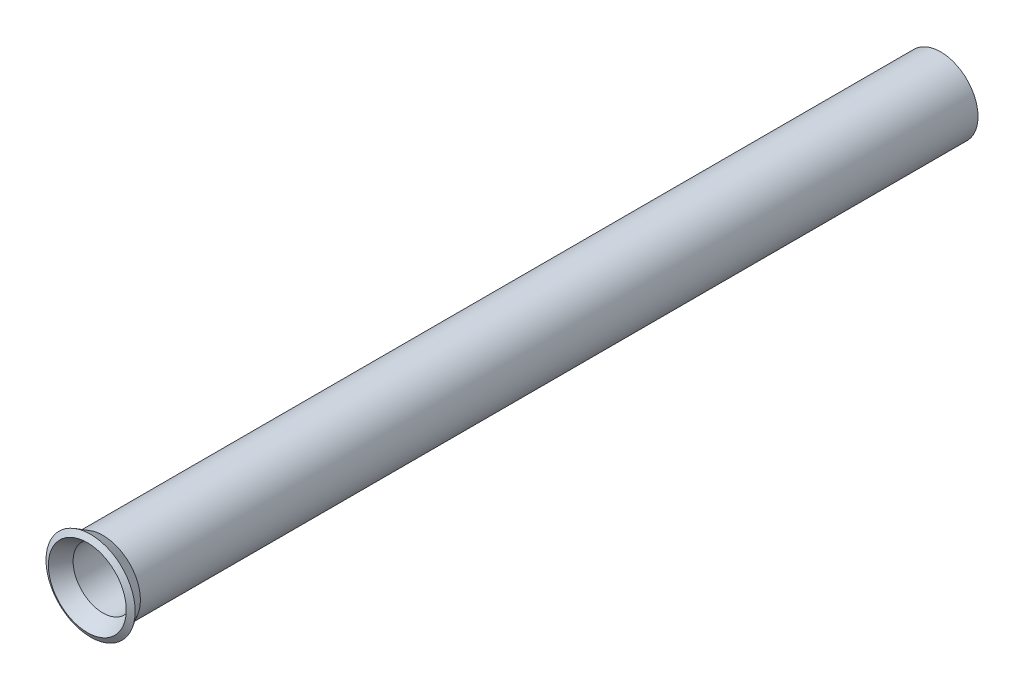
SolidWorks part; units mm, degrees
material "Stainless Steel (ferritic)"
ref_plane "Front Plane" through (0, 0, 0) normal (0, 0, 1) x (1, 0, 0)
ref_plane "Top Plane" through (0, 0, 0) normal (0, 1, 0) x (1, 0, 0)
ref_plane "Right Plane" through (0, 0, 0) normal (1, 0, 0) x (0, 0, -1)
sketch "Sketch1" plane through (0, 0, 0) normal (0, 0, 1) x (1, 0, 0)
  circle A0 centre (0, 0) radius 1.27
  circle A1 centre (0, 0) radius 1.5875
  dimension "D1" = 2.54
  dimension "D2" = 3.175
extrude "Boss-Extrude1" add sketch "Sketch1" along normal blind 35.56
sketch "Sketch2" plane through (0, 0, 0) normal (0, 1, 0) x (1, 0, 0)
  line L0 (1.5875, -35.56) -> (1.8923, -36.0879)
  line L1 (1.8923, -36.0879) -> (1.6542, -36.2254)
  line L2 (1.6542, -36.2254) -> (1.27, -35.56)
  line L3 (1.27, -35.56) -> (1.5875, -35.56)
  line L5 (1.5875, -35.56) -> (1.5875, 0) construction
  line L6 (0, -35.56) -> (0, -36.3125) construction
  line L7 (-1.27, -35.56) -> (1.27, -35.56) construction
  dimension "D1" = 0.3048
  dimension "D2" = 150
revolve "Revolve1" add sketch "Sketch2" angle 360 about L6
